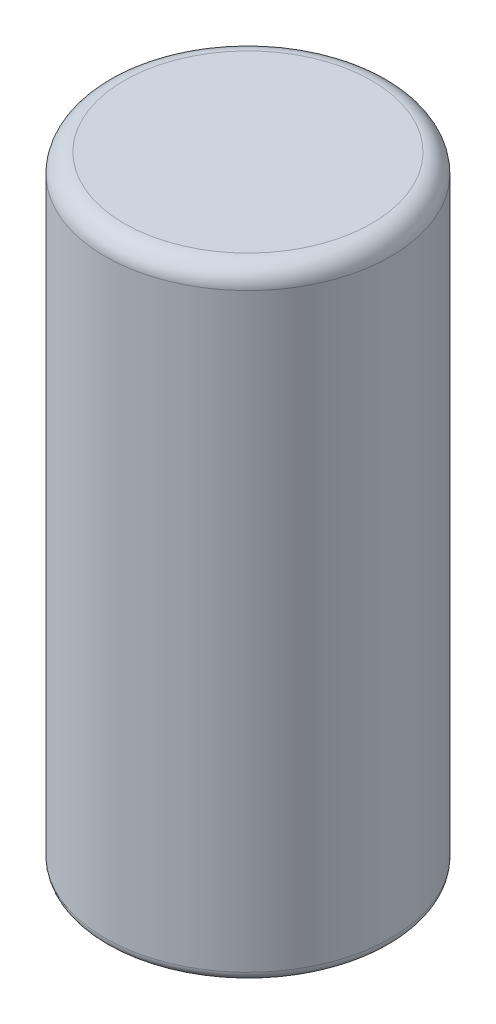
SolidWorks part; units mm, degrees
ref_plane "Front Plane" through (0, 0, 0) normal (0, 0, 1) x (1, 0, 0)
ref_plane "Top Plane" through (0, 0, 0) normal (0, 1, 0) x (1, 0, 0)
ref_plane "Right Plane" through (0, 0, 0) normal (1, 0, 0) x (0, 0, -1)
sketch "Sketch1" plane through (0, 0, 0) normal (0, 1, 0) x (1, 0, 0)
  circle A0 centre (0, 0) radius 15
extrude "Boss-Extrude1" add sketch "Sketch1" along normal blind 65
fillet "Fillet1" radius 2 1 edges at (0, 65, 15)
fillet "Fillet2" radius 1 1 edges at (0, 0, 15)
sketch "Sketch2" plane through (0, 0, 0) normal (0, -1, 0) x (-1, 0, 0)
  circle A0 centre (6, 0) radius 2
  circle A1 centre (-6, 0) radius 2
  dimension "D1" = 6
  dimension "D2" = 6
extrude "Boss-Extrude2" add sketch "Sketch2" along normal blind 5 draft 16
